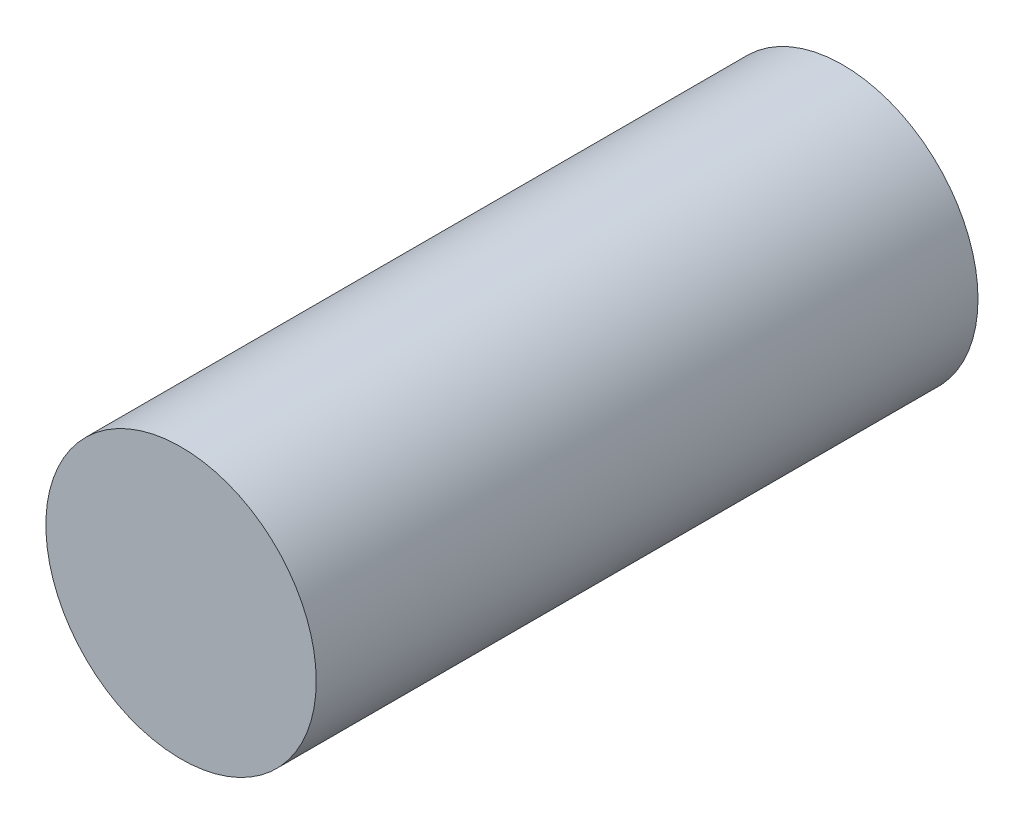
SolidWorks part; units mm, degrees
ref_plane "Front Plane" through (0, 0, 0) normal (0, 0, 1) x (1, 0, 0)
ref_plane "Top Plane" through (0, 0, 0) normal (0, 1, 0) x (1, 0, 0)
ref_plane "Right Plane" through (0, 0, 0) normal (1, 0, 0) x (0, 0, -1)
sketch "Sketch1" plane through (0, 0, 0) normal (0, 0, 1) x (1, 0, 0)
  circle A0 centre (0, 0) radius 2.95
  dimension "D1" = 5.9
extrude "Boss-Extrude1" add sketch "Sketch1" along normal blind 14.44
